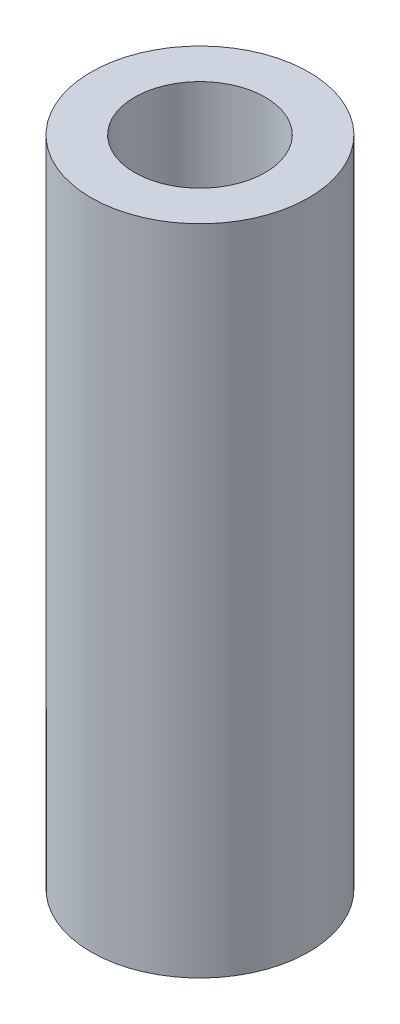
SolidWorks part; units mm, degrees
ref_plane "정면" through (0, 0, 0) normal (0, 0, 1) x (1, 0, 0)
ref_plane "윗면" through (0, 0, 0) normal (0, 1, 0) x (1, 0, 0)
ref_plane "우측면" through (0, 0, 0) normal (1, 0, 0) x (0, 0, -1)
sketch "스케치1" plane through (0, 0, 0) normal (0, 1, 0) x (1, 0, 0)
  circle A0 centre (0, 0) radius 25
  dimension "D1" = 50
extrude "보스-돌출1" add sketch "스케치1" along normal mid plane 150
sketch "스케치2" plane through (0, 75, 0) normal (0, 1, 0) x (1, 0, 0)
  circle A0 centre (0, 0) radius 15
  dimension "D1" = 30
extrude "컷-돌출1" cut sketch "스케치2" against normal through all
